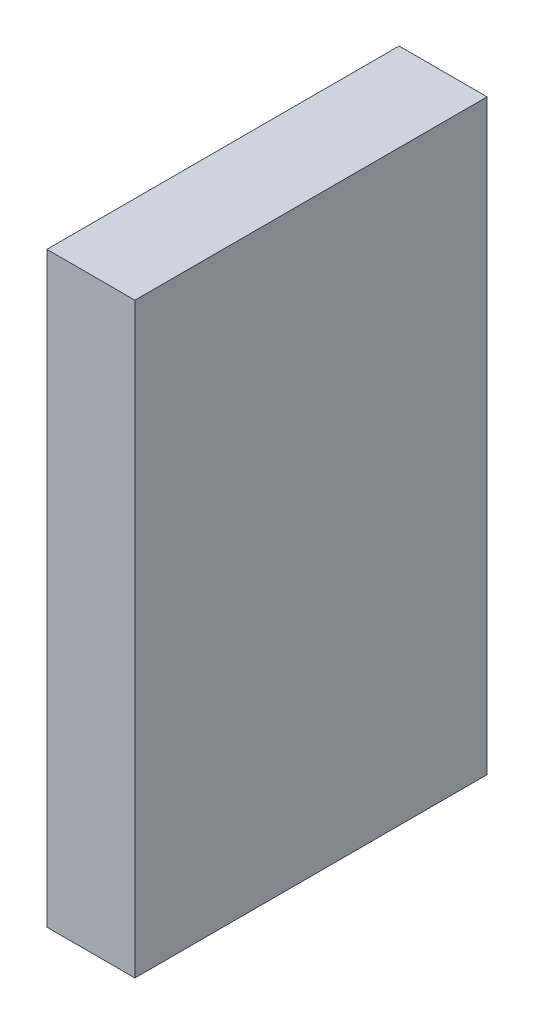
SolidWorks part; units mm, degrees
ref_plane "Front Plane" through (0, 0, 0) normal (0, 0, 1) x (1, 0, 0)
ref_plane "Top Plane" through (0, 0, 0) normal (0, 1, 0) x (1, 0, 0)
ref_plane "Right Plane" through (0, 0, 0) normal (1, 0, 0) x (0, 0, -1)
other "Configuration Table"
sketch "Sketch1" plane through (0, 0, 0) normal (0, 0, 1) x (1, 0, 0)
  line L1 (0, 0) -> (15, 0)
  line L2 (0, 0) -> (0, 100)
  line L3 (0, 100) -> (15, 100)
  line L4 (15, 0) -> (15, 100)
  dimension "D1" = 100
  dimension "D2" = 15
extrude "Extrude1" add sketch "Sketch1" along normal blind 60
